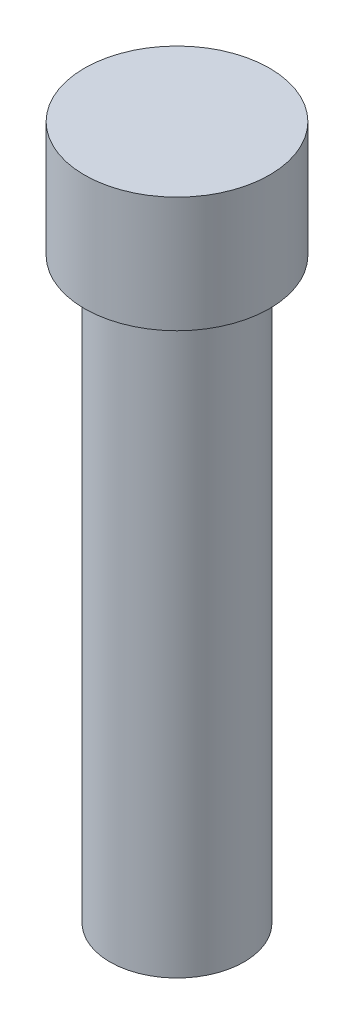
SolidWorks part; units mm, degrees
ref_plane "前视基准面" through (0, 0, 0) normal (0, 0, 1) x (1, 0, 0)
ref_plane "上视基准面" through (0, 0, 0) normal (0, 1, 0) x (1, 0, 0)
ref_plane "右视基准面" through (0, 0, 0) normal (1, 0, 0) x (0, 0, -1)
other "Configuration Table"
sketch "草图1" plane through (0, 0, 0) normal (0, 1, 0) x (1, 0, 0)
  circle A0 centre (0, 0) radius 2.9
  dimension "D1" = 5.8
extrude "凸台-拉伸1" add sketch "草图1" along normal blind 25 contours A0
sketch "草图2" plane through (0, 25, 0) normal (0, 1, 0) x (1, 0, 0)
  circle A0 centre (0, 0) radius 4
  dimension "D1" = 8
extrude "凸台-拉伸2" add sketch "草图2" along normal blind 5
